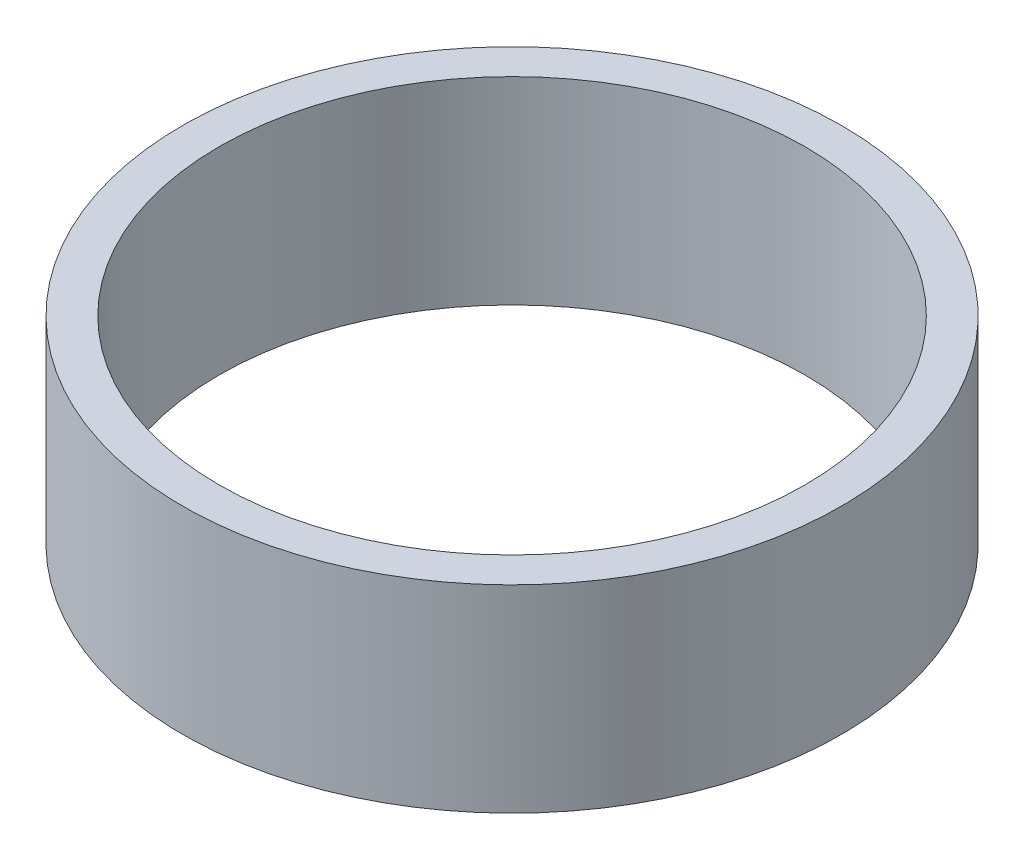
SolidWorks part; units mm, degrees
material "6061-T6 (SS)"
ref_plane "Front Plane" through (0, 0, 0) normal (0, 0, 1) x (1, 0, 0)
ref_plane "Top Plane" through (0, 0, 0) normal (0, 1, 0) x (1, 0, 0)
ref_plane "Right Plane" through (0, 0, 0) normal (1, 0, 0) x (0, 0, -1)
sketch "Sketch1" plane through (0, 0, 0) normal (1, 0, 0) x (0, 0, -1)
  line L0 (0, 0) -> (0, 23.9672) construction
  line L2 (12.7, 0) -> (14.2875, 0)
  line L3 (12.7, 0) -> (12.7, 8.5725)
  line L4 (12.7, 8.5725) -> (14.2875, 8.5725)
  line L5 (14.2875, 0) -> (14.2875, 8.5725)
  dimension "D1" = 25.4
  dimension "D2" = 28.575
  dimension "D3" = 8.5725
revolve "Revolve1" add sketch "Sketch1" angle 360 about L0
